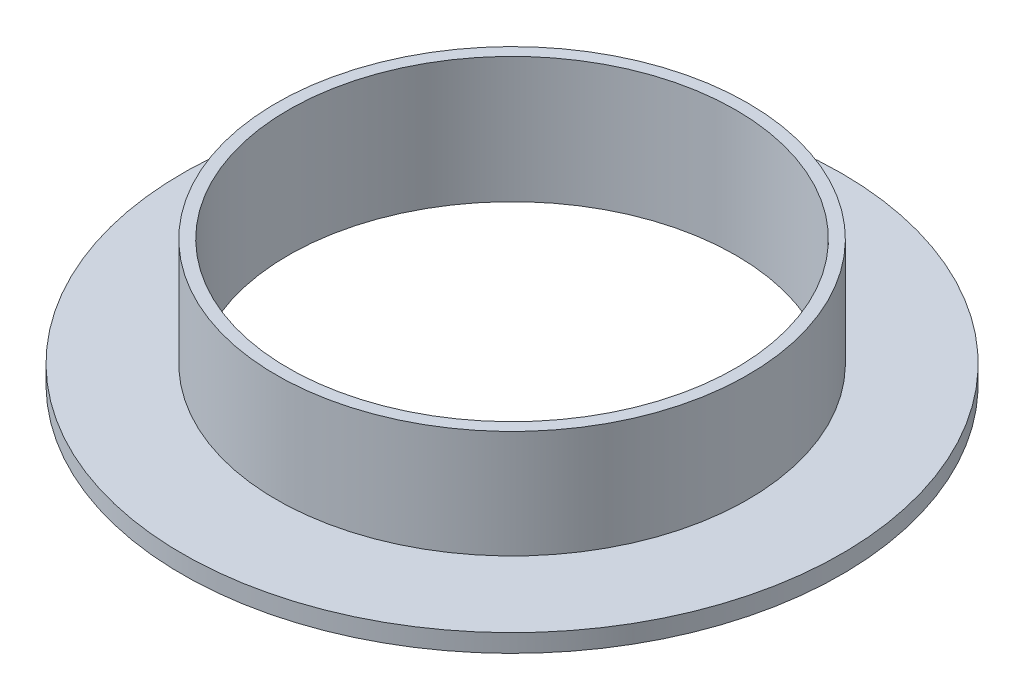
SolidWorks part; units mm, degrees
ref_plane "Plan de face" through (0, 0, 0) normal (0, 0, 1) x (1, 0, 0)
ref_plane "Plan de dessus" through (0, 0, 0) normal (0, 1, 0) x (1, 0, 0)
ref_plane "Plan de droite" through (0, 0, 0) normal (1, 0, 0) x (0, 0, -1)
sketch "Esquisse1" plane through (0, 0, 0) normal (0, 0, 1) x (1, 0, 0)
  line L0 (0, 0) -> (0, 31.9169) construction
  line L1 (-16.5, 0) -> (-11.2, 0)
  line L2 (-11.2, 0) -> (-11.2, 6.3)
  line L3 (-11.2, 6.3) -> (-11.8, 6.3)
  line L4 (-11.8, 6.3) -> (-11.8, 0.9)
  line L5 (-11.8, 0.9) -> (-16.5, 0.9)
  line L6 (-16.5, 0.9) -> (-16.5, 0)
  dimension "D1" = 33
  dimension "D2" = 22.4
  dimension "D3" = 6.3
  dimension "D4" = 5.4
  dimension "D5" = 23.6
revolve "Révolution1" add sketch "Esquisse1" angle 360 about L0
